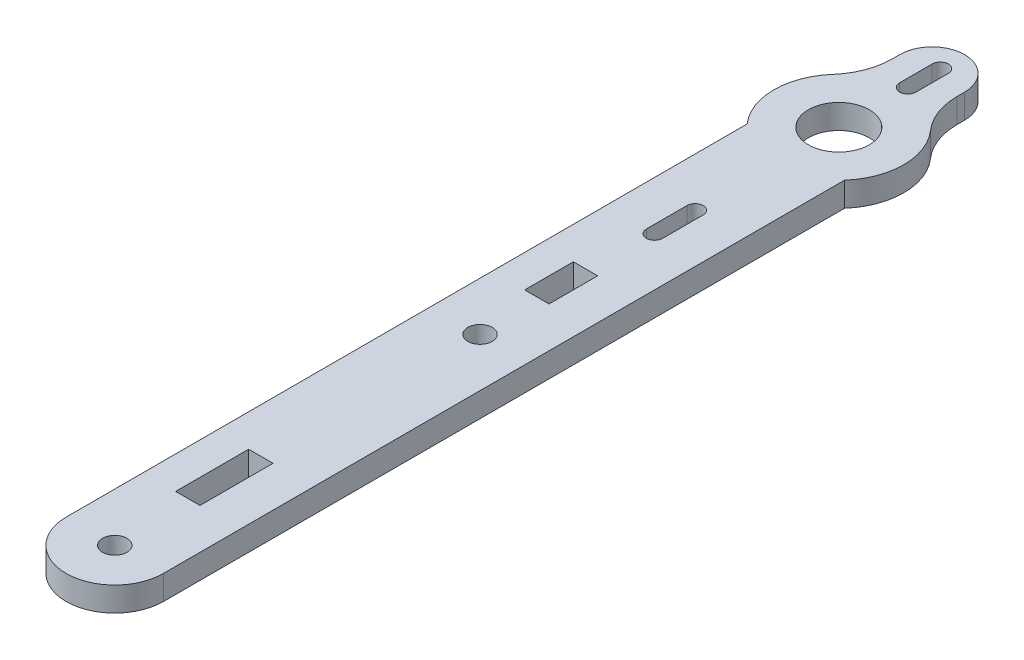
SolidWorks part; units mm, degrees
ref_plane "Alzado" through (0, 0, 0) normal (0, 0, 1) x (1, 0, 0)
ref_plane "Planta" through (0, 0, 0) normal (0, 1, 0) x (1, 0, 0)
ref_plane "Vista lateral" through (0, 0, 0) normal (1, 0, 0) x (0, 0, -1)
sketch "Croquis1" plane through (0, 0, 0) normal (0, 0, 1) x (1, 0, 0)
  line L0 (41777.5435, -351.026) -> (41777.5435, -434.9395)
  line L1 (41765.5435, -351.026) -> (41765.5435, -434.9395)
  line L2 (41775.5435, -334.2345) -> (41775.5435, -335.1514)
  line L3 (41767.5435, -334.2345) -> (41767.5435, -335.1514)
  line L4 (41772.5435, -333.2345) -> (41772.5435, -337.2345)
  line L5 (41770.5435, -333.2345) -> (41770.5435, -337.2345)
  line L6 (41772.5435, -363.4395) -> (41772.5435, -368.4395)
  line L7 (41770.5435, -363.4395) -> (41770.5435, -368.4395)
  line L9 (41769.5435, -376.4395) -> (41772.5435, -376.4395)
  line L10 (41769.5435, -376.4395) -> (41769.5435, -382.4395)
  line L11 (41769.5435, -382.4395) -> (41772.5435, -382.4395)
  line L12 (41772.5435, -376.4395) -> (41772.5435, -382.4395)
  line L13 (41769.5435, -416.4395) -> (41772.5435, -416.4395)
  line L14 (41769.5435, -416.4395) -> (41769.5435, -425.4395)
  line L15 (41769.5435, -425.4395) -> (41772.5435, -425.4395)
  line L16 (41772.5435, -416.4395) -> (41772.5435, -425.4395)
  circle A0 centre (41771.5435, -434.9395) radius 1.5
  arc A1 (41765.5435, -434.9395) -> (41777.5435, -434.9395) centre (41771.5435, -434.9395) ccw
  circle A2 centre (41771.5435, -389.9395) radius 1.5
  arc A3 (41770.5435, -368.4395) -> (41772.5435, -368.4395) centre (41771.5435, -368.4395) ccw
  arc A4 (41772.5435, -363.4395) -> (41770.5435, -363.4395) centre (41771.5435, -363.4395) ccw
  circle A5 centre (41771.5435, -345.7345) radius 3.75
  arc A7 (41775.5435, -335.1514) -> (41777.5435, -340.4429) centre (41783.5435, -335.1514) ccw
  arc A8 (41765.5435, -340.4429) -> (41767.5435, -335.1514) centre (41759.5435, -335.1514) ccw
  arc A9 (41772.5435, -333.2345) -> (41770.5435, -333.2345) centre (41771.5435, -333.2345) ccw
  arc A10 (41770.5435, -337.2345) -> (41772.5435, -337.2345) centre (41771.5435, -337.2345) ccw
  arc A12 (41775.5435, -334.2345) -> (41767.5435, -334.2345) centre (41771.5435, -334.2345) ccw
  arc A13 (41765.5435, -340.4429) -> (41765.5435, -351.026) centre (41771.5435, -345.7345) ccw
  arc A14 (41777.5435, -351.026) -> (41777.5435, -340.4429) centre (41771.5435, -345.7345) ccw
extrude "Saliente-Extruir1" add sketch "Croquis1" along normal blind 3
move or copy body "Sólido-Mover/Copiar1" bodies to move or copy 101 copy no rotation origin (0, -385.587, 1.5) rotation axis (-1, 0, 0) rotation angle 90
